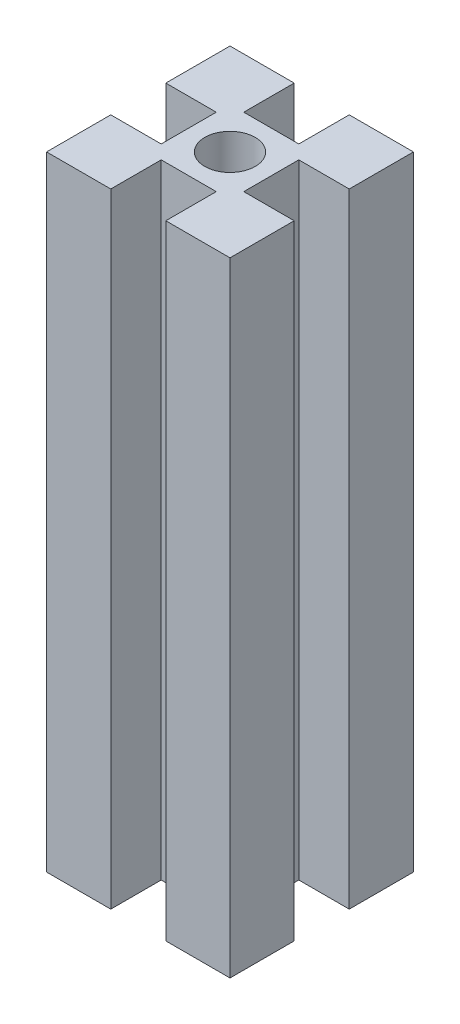
SolidWorks part; units mm, degrees
ref_plane "Front Plane" through (0, 0, 0) normal (0, 0, 1) x (1, 0, 0)
ref_plane "Top Plane" through (0, 0, 0) normal (0, 1, 0) x (1, 0, 0)
ref_plane "Right Plane" through (0, 0, 0) normal (1, 0, 0) x (0, 0, -1)
sketch "Sketch1" plane through (0, 0, 0) normal (0, 1, 0) x (1, 0, 0)
  line L1 (10, -10) -> (-10, -10)
  line L2 (10, -10) -> (10, 10)
  line L3 (10, 10) -> (-10, 10)
  line L4 (-10, -10) -> (-10, 10)
  line L5 (10, -10) -> (-10, 10) construction
  line L6 (10, 10) -> (-10, -10) construction
  point P0 (0, 0)
  dimension "D1" = 20
  dimension "D2" = 20
extrude "Body" add sketch "Sketch1" along normal blind 68
sketch "Sketch2" plane through (0, 68, 0) normal (0, 1, 0) x (1, 0, 0)
  line L0 (10, 10) -> (-10, 10) construction
  line L1 (-3, 10) -> (3, 10)
  line L2 (-3, 10) -> (-3, 4.5)
  line L3 (-3, 4.5) -> (3, 4.5)
  line L4 (3, 10) -> (3, 4.5)
  line L5 (10, 3) -> (10, -3)
  line L6 (10, 3) -> (4.5, 3)
  line L7 (4.5, 3) -> (4.5, -3)
  line L8 (10, -3) -> (4.5, -3)
  line L9 (3, -10) -> (-3, -10)
  line L10 (3, -10) -> (3, -4.5)
  line L11 (3, -4.5) -> (-3, -4.5)
  line L12 (-3, -10) -> (-3, -4.5)
  line L13 (-10, -3) -> (-10, 3)
  line L14 (-10, -3) -> (-4.5, -3)
  line L15 (-4.5, -3) -> (-4.5, 3)
  line L16 (-10, 3) -> (-4.5, 3)
  circle A0 centre (0, 0) radius 2.75
  point P10 (0, 4.5)
  point P25 (0, 0)
  dimension "D1" = 5.5
  dimension "D2" = 5.5
  dimension "D3" = 6
  dimension "D4" = 4
extrude "Profil" cut sketch "Sketch2" against normal through all
